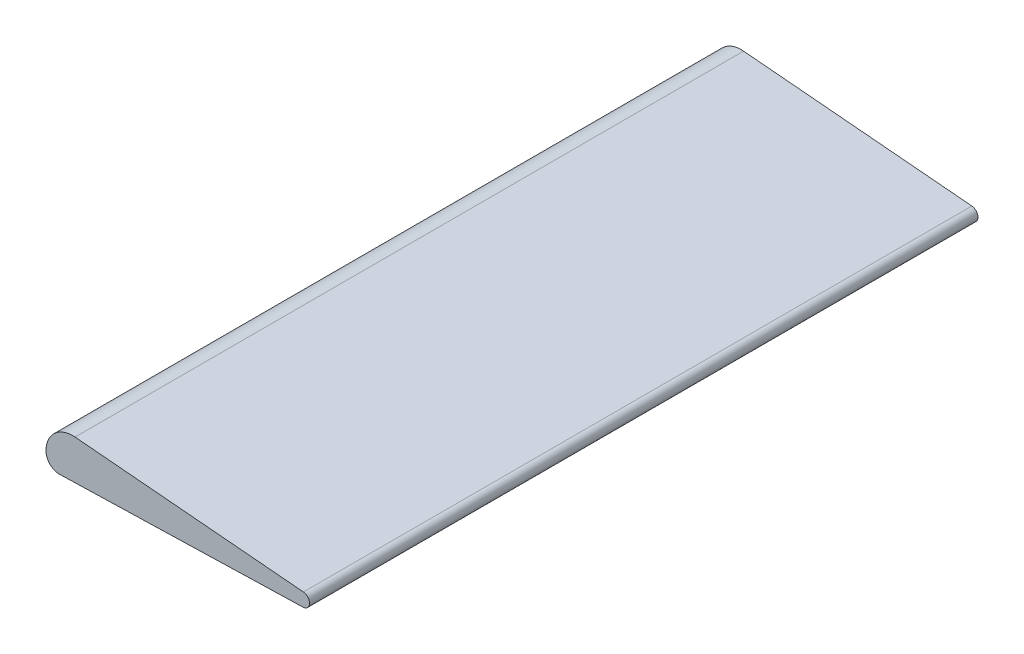
SolidWorks part; units mm, degrees
ref_plane "Front Plane" through (0, 0, 0) normal (0, 0, 1) x (1, 0, 0)
ref_plane "Top Plane" through (0, 0, 0) normal (0, 1, 0) x (1, 0, 0)
ref_plane "Right Plane" through (0, 0, 0) normal (1, 0, 0) x (0, 0, -1)
sketch "Sketch1" plane through (0, 0, 0) normal (0, 0, 1) x (1, 0, 0)
  line L0 (0, 0) -> (9.759, 0) construction
  line L1 (1.1046, 1.0121) -> (9.7811, 0.253)
  line L2 (0.5219, -0.5078) -> (9.7659, -0.2539)
  line L3 (0, 0) -> (0, -0.5078) construction
  line L4 (0, -0.5078) -> (0.5219, -0.5078) construction
  arc A0 (1.1046, 1.0121) -> (0, 0) centre (1.016, 0) ccw
  arc A1 (0, 0) -> (0.5219, -0.5078) centre (0.508, 0) ccw
  arc A2 (9.7659, -0.2539) -> (9.7811, 0.253) centre (9.759, 0) ccw
  point P10 (0, 0)
  point P12 (9.6668, 0)
  dimension "D1" = 1.016
  dimension "D2" = 0.508
  dimension "D4" = 0.254
  dimension "D3" = 5
extrude "Boss-Extrude1" add sketch "Sketch1" along normal mid plane 25.4
